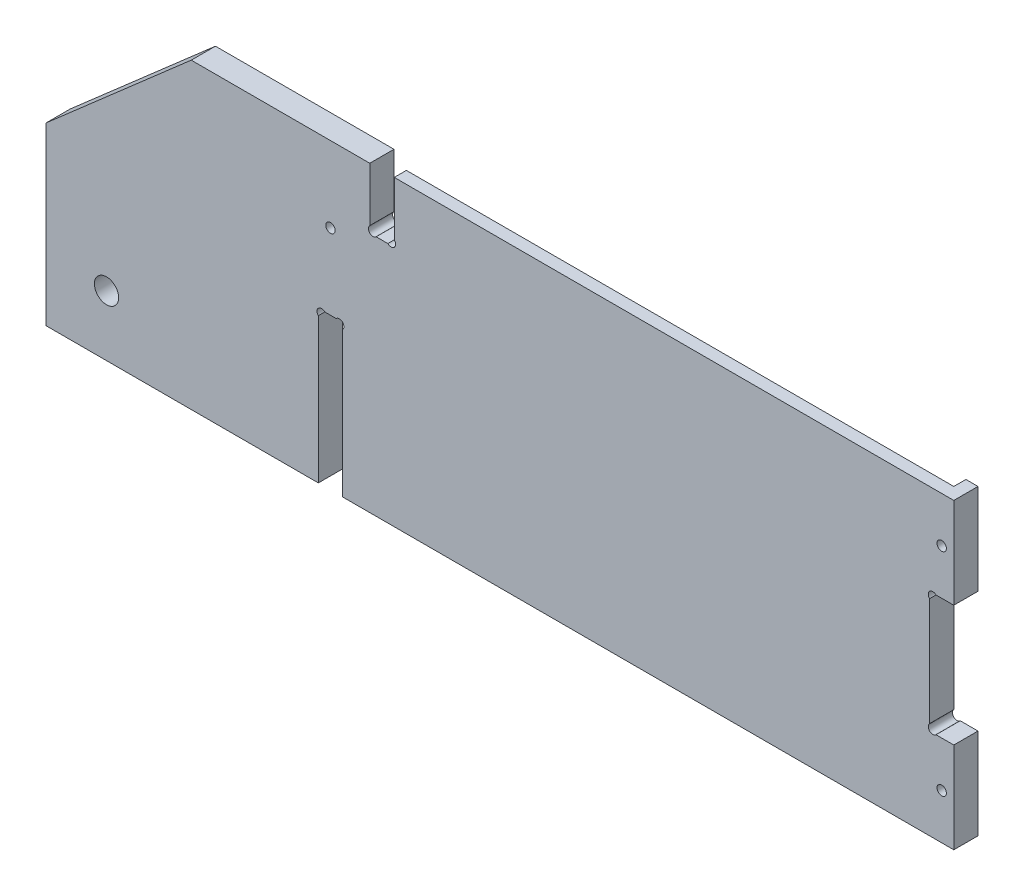
SolidWorks part; units mm, degrees
ref_plane "Plan de face" through (0, 0, 0) normal (0, 0, 1) x (1, 0, 0)
ref_plane "Plan de dessus" through (0, 0, 0) normal (0, 1, 0) x (1, 0, 0)
ref_plane "Plan de droite" through (0, 0, 0) normal (1, 0, 0) x (0, 0, -1)
sketch "Esquisse1" plane through (0, 0, 0) normal (0, 0, 1) x (1, 0, 0)
  line L0 (-31.0143, 75.0386) -> (47.9657, 75.0386) construction
  line L1 (-2.0343, 64.481) -> (56.9657, 64.481)
  line L2 (-50.0343, 22.5129) -> (-50.0343, -35.519)
  line L3 (-50.0343, -35.519) -> (39.9657, -35.519)
  line L4 (249.9657, 64.481) -> (249.9657, 34.481)
  line L5 (47.9657, -33.6612) -> (47.9657, 94.1344) construction
  line L6 (47.9657, -35.519) -> (47.9657, 12.3597)
  line L7 (42.087, 14.481) -> (45.8444, 14.481)
  line L8 (39.9657, -35.519) -> (39.9657, 12.3597)
  line L9 (47.9657, -35.519) -> (249.9657, -35.519)
  line L10 (245.9657, 75.0386) -> (60.9657, 75.0386) construction
  line L11 (39.9657, -34.0836) -> (39.9657, 100.8603) construction
  line L12 (-50.0343, 22.5129) -> (-2.0343, 64.481)
  line L13 (245.9657, -38.4602) -> (245.9657, 75.0386) construction
  line L14 (60.9657, 91.8154) -> (60.9657, -35.9801) construction
  line L15 (56.9657, 64.481) -> (56.9657, 46.626)
  line L16 (62.9354, 44.481) -> (59.063, 44.481)
  line L17 (65.0567, 46.6023) -> (65.0567, 64.481)
  line L18 (65.0567, 64.481) -> (249.9657, 64.481)
  line L19 (283.5481, 14.481) -> (224.3033, 14.481) construction
  line L20 (241.9657, -3.3977) -> (241.9657, 32.3597)
  line L21 (244.087, 34.481) -> (249.9657, 34.481)
  line L22 (244.087, -5.519) -> (249.9657, -5.519)
  line L23 (249.9657, -5.519) -> (249.9657, -35.519)
  line L24 (249.9657, 64.481) -> (241.9657, 34.481) construction
  line L25 (249.9657, -35.519) -> (241.9657, -5.519) construction
  line L26 (245.9657, 30.0585) -> (248.9274, 26.6712) construction
  line L27 (133.9372, 64.481) -> (133.9372, -35.519) construction
  line L28 (133.9372, 14.481) -> (267.943, 14.481) construction
  line L29 (43.9657, 14.481) -> (43.9657, 64.481) construction
  arc A0 (62.9354, 44.481) -> (65.0567, 46.6023) centre (63.9961, 45.5416) ccw
  arc A1 (56.9657, 46.626) -> (59.063, 44.481) centre (58.0144, 45.5535) ccw
  arc A2 (42.087, 14.481) -> (39.9657, 12.3597) centre (41.0264, 13.4203) ccw
  arc A3 (47.9657, 12.3597) -> (45.8444, 14.481) centre (46.905, 13.4203) ccw
  arc A4 (244.087, 34.481) -> (241.9657, 32.3597) centre (243.0264, 33.4203) ccw
  arc A5 (241.9657, -3.3977) -> (244.087, -5.519) centre (243.0264, -4.4584) ccw
  circle A6 centre (245.9657, 49.481) radius 1.55
  circle A7 centre (245.9657, -20.519) radius 1.55
  circle A8 centre (43.9657, 39.481) radius 1.55
  point P30 (251.9657, 14.481)
  dimension "D5" = 40
  dimension "D6" = 1.5
  dimension "D7" = 1.5
  dimension "D8" = 1.5
  dimension "D9" = 1.5
  dimension "D10" = 8
  dimension "D11" = 300
  dimension "D1" = 4
  dimension "D2" = 4
  dimension "D3" = 185
  dimension "D4" = 100
  dimension "D12" = 50
  dimension "D13" = 90
  dimension "D14" = 8
  dimension "D15" = 8
extrude "Boss.-Extru.1" add sketch "Esquisse1" along normal blind 8
sketch "Esquisse2" plane through (0, 0, 0) normal (0, 0, -1) x (-1, 0, 0)
  line L0 (-65.0567, 64.481) -> (-249.9657, 64.481) construction
  line L1 (-245.9657, 64.481) -> (-60.9657, 64.481)
  line L2 (-245.9657, 64.481) -> (-245.9657, 54.6023)
  line L3 (-243.8444, 52.481) -> (-60.9657, 52.481)
  line L4 (-60.9657, 91.8154) -> (-60.9657, -35.9801) construction
  line L5 (-245.9657, -38.4602) -> (-245.9657, 75.0386) construction
  line L7 (-60.9657, 52.481) -> (-60.9657, 64.481)
  arc A0 (-245.9657, 54.6023) -> (-243.8444, 52.481) centre (-244.905, 53.5416) ccw
extrude "Enlèv. mat.-Extru.1" cut sketch "Esquisse2" against normal blind 4
sketch "Esquisse3" plane through (0, 0, 0) normal (0, 0, -1) x (-1, 0, 0)
  line L0 (30.0343, -35.519) -> (30.0343, -15.519) construction
  line L1 (50.0343, -35.519) -> (-39.9657, -35.519) construction
  line L2 (50.0343, 22.5129) -> (50.0343, -35.519) construction
  circle A0 centre (30.0343, -15.519) radius 4
  dimension "D1" = 20
extrude "Enlèv. mat.-Extru.2" cut sketch "Esquisse3" against normal blind 38
